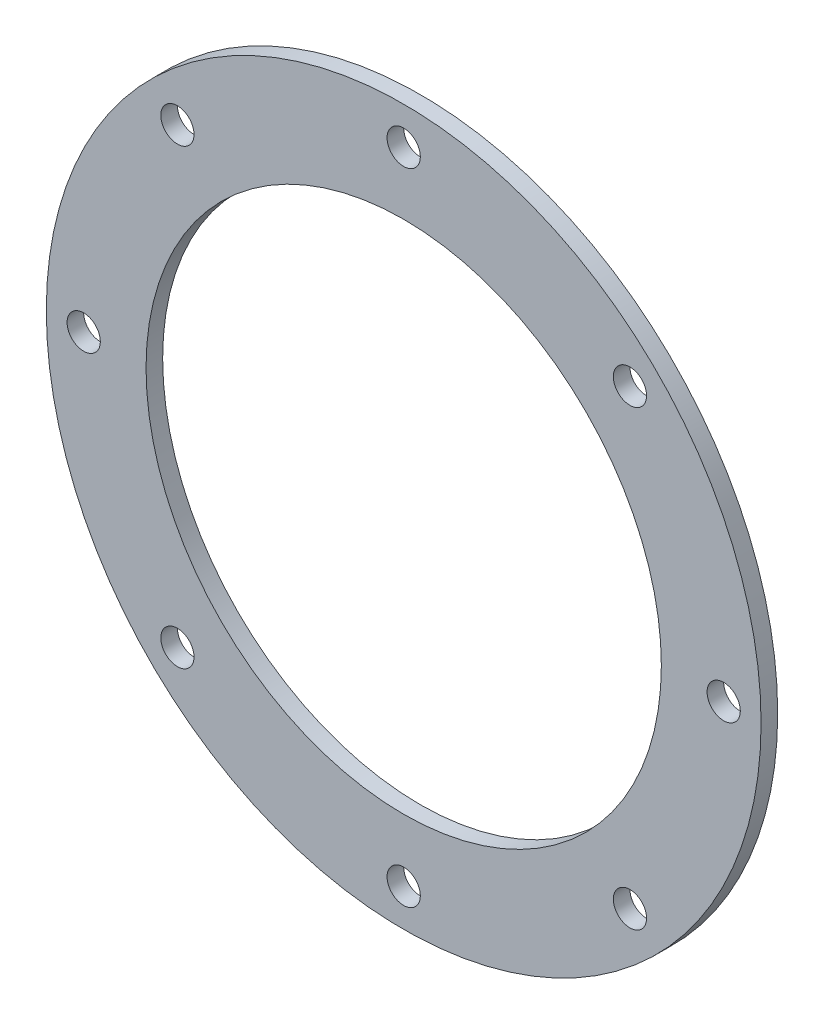
SolidWorks part; units mm, degrees
ref_plane "Front Plane" through (0, 0, 0) normal (0, 0, 1) x (1, 0, 0)
ref_plane "Top Plane" through (0, 0, 0) normal (0, 1, 0) x (1, 0, 0)
ref_plane "Right Plane" through (0, 0, 0) normal (1, 0, 0) x (0, 0, -1)
sketch "Sketch1" plane through (0, 0, 0) normal (0, 0, 1) x (1, 0, 0)
  line L0 (82.361, 0) -> (26.6862, 0) construction
  line L1 (-41.821, 10) -> (-99.0936, 10)
  line L2 (-99.0936, 10) -> (-99.0936, -10)
  line L3 (-99.0936, -10) -> (-41.821, -10)
  line L4 (41.821, 10) -> (82.361, 10)
  line L5 (82.361, 10) -> (82.361, -10)
  line L6 (82.361, -10) -> (41.821, -10)
  line L7 (-43, 0) -> (-99.0936, 0) construction
  circle A0 centre (0, 0) radius 31
  arc A1 (41.821, 10) -> (-41.821, 10) centre (0, 0) ccw
  arc A2 (-41.821, -10) -> (41.821, -10) centre (0, 0) ccw
  circle A3 centre (0, 38.5) radius 2
  circle A4 centre (27.2236, 27.2236) radius 2
  circle A5 centre (38.5, 0) radius 2
  circle A6 centre (27.2236, -27.2236) radius 2
  circle A7 centre (0, -38.5) radius 2
  circle A8 centre (-27.2236, -27.2236) radius 2
  circle A9 centre (-38.5, 0) radius 2
  circle A10 centre (-27.2236, 27.2236) radius 2
  arc A11 (-41.821, 10) -> (-41.6841, -10.5564) centre (0, 0) ccw
  arc A12 (41.821, 10) -> (41.8102, -10.0453) centre (0, 0) cw
  point P7 (0, 0)
  point P19 (-99.0936, 0)
  point P35 (0, 0)
  dimension "D1" = 4
  dimension "D3" = 62
  dimension "D4" = 43
  dimension "D2" = 38.5
  dimension "D6" = 20
  dimension "D5" = 8
extrude "Boss-Extrude1" add sketch "Sketch1" along normal mid plane 2 contours A12 A1 A11 A2 A10 A9 A8 A7 A6 A5 A4 A3 A0
